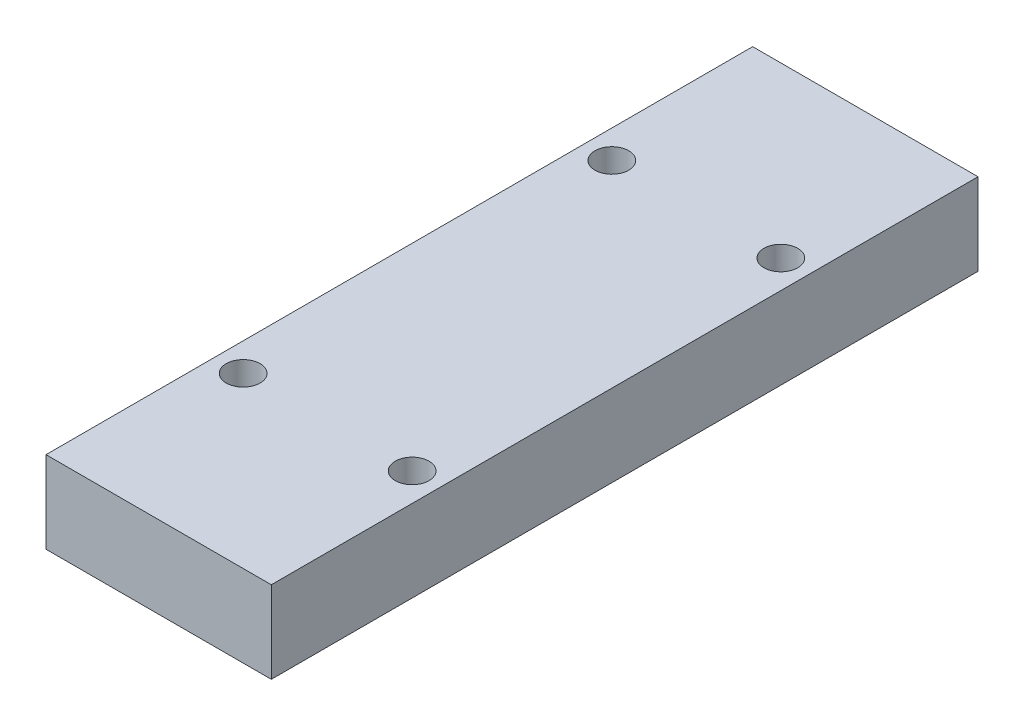
SolidWorks part; units mm, degrees
material "6061 合金"
ref_plane "前视基准面" through (0, 0, 0) normal (0, 0, 1) x (1, 0, 0)
ref_plane "上视基准面" through (0, 0, 0) normal (0, 1, 0) x (1, 0, 0)
ref_plane "右视基准面" through (0, 0, 0) normal (1, 0, 0) x (0, 0, -1)
sketch "草图1" plane through (0, 0, 0) normal (0, 0, 1) x (1, 0, 0)
  line L1 (-11, 4) -> (11, 4)
  line L2 (-11, 4) -> (-11, -4)
  line L3 (-11, -4) -> (11, -4)
  line L4 (11, 4) -> (11, -4)
  line L5 (-11, 4) -> (11, -4) construction
  line L6 (-11, -4) -> (11, 4) construction
  point P0 (0, 0)
  dimension "D1" = 8
  dimension "D2" = 22
extrude "凸台-拉伸1" add sketch "草图1" along normal blind 69
sketch "草图2" plane through (0, 4, 0) normal (0, 1, 0) x (1, 0, 0)
  line L0 (0, 0) -> (0, -69) construction
  line L1 (11, -69) -> (-11, -69) construction
  line L3 (-8.25, -16.5) -> (8.25, -16.5) construction
  line L4 (-8.25, -16.5) -> (-8.25, -52.5) construction
  line L5 (-8.25, -52.5) -> (8.25, -52.5) construction
  line L6 (8.25, -16.5) -> (8.25, -52.5) construction
  line L7 (-8.25, -16.5) -> (8.25, -52.5) construction
  line L8 (-8.25, -52.5) -> (8.25, -16.5) construction
  point P5 (0, -34.5)
  dimension "D1" = 36
  dimension "D2" = 16.5
hole_wizard "M4 螺纹孔1" positions "3D草图1" profile "草图3" tap size "M4" standard "IS"
sketch3d "3D草图1"
  point P0 (-8.25, 4, 16.5)
  point P3 (8.25, 4, 16.5)
  point P6 (8.25, 4, 52.5)
  point P9 (-8.25, 4, 52.5)
cosmetic thread "孔螺蚊线1" parameters "D2"=4
cosmetic thread "孔螺蚊线2" parameters "D2"=4
cosmetic thread "孔螺蚊线3" parameters "D2"=4
cosmetic thread "孔螺蚊线4" parameters "D2"=4
sketch "草图3" plane through (-8.25, 4, 16.5) normal (1, 0, 0) x (0, 0, 1)
  line L0 (0, 0) -> (0, 7.9914)
  line L1 (0, 7.9914) -> (1.65, 7)
  line L2 (1.65, 7) -> (1.65, 0)
  line L5 (1.65, 0) -> (0, 0)
  line L10 (0, 7.9914) -> (-1.65, 7) construction
  line L11 (0, -6.35) -> (0, 107.95) construction
  dimension "螺纹孔钻头直径" = 3.3
  dimension "螺纹孔钻头深度" = 7
  dimension "导头角度" = 118
